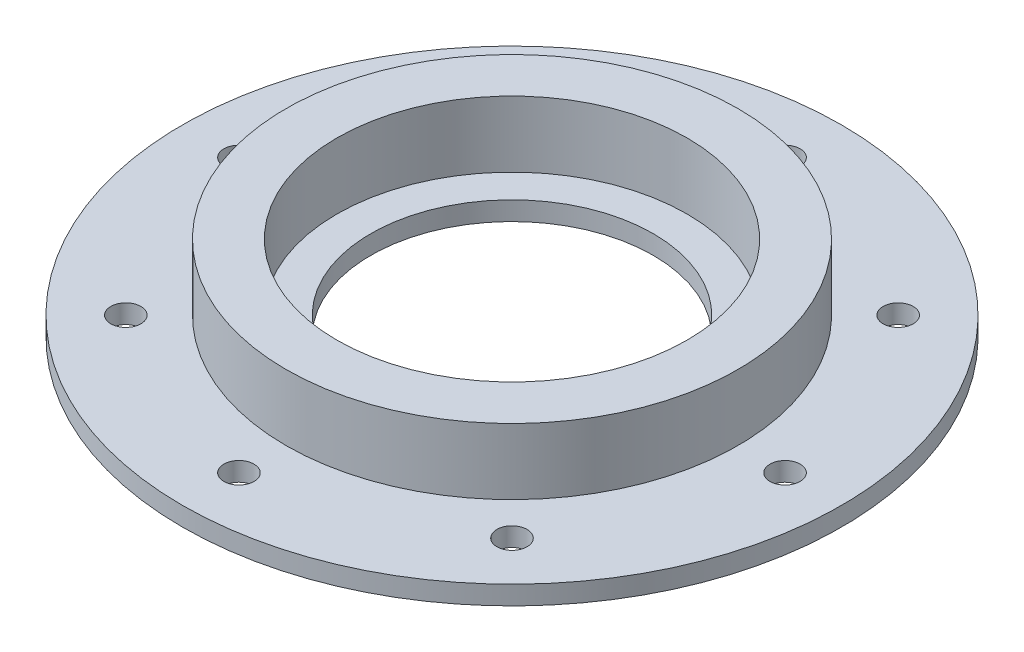
SolidWorks part; units mm, degrees
ref_plane "前视基准面" through (0, 0, 0) normal (0, 0, 1) x (1, 0, 0)
ref_plane "上视基准面" through (0, 0, 0) normal (0, 1, 0) x (1, 0, 0)
ref_plane "右视基准面" through (0, 0, 0) normal (1, 0, 0) x (0, 0, -1)
sketch "草图1" plane through (0, 0, 0) normal (0, 1, 0) x (1, 0, 0)
  line L0 (0, 0) -> (29, 0) construction
  circle A0 centre (0, 0) radius 15
  circle A1 centre (0, 0) radius 35
  circle A2 centre (29, 0) radius 1.6
  circle A3 centre (20.5061, -20.5061) radius 1.6
  circle A4 centre (0, -29) radius 1.6
  circle A5 centre (-20.5061, -20.5061) radius 1.6
  circle A6 centre (-29, 0) radius 1.6
  circle A7 centre (-20.5061, 20.5061) radius 1.6
  circle A8 centre (0, 29) radius 1.6
  circle A9 centre (20.5061, 20.5061) radius 1.6
  dimension "D1" = 70
  dimension "D2" = 30
  dimension "D3" = 3.2
  dimension "D4" = 29
  dimension "D5" = 8
extrude "凸台-拉伸1" add sketch "草图1" against normal blind 2
sketch "草图2" plane through (0, 0, 0) normal (0, 1, 0) x (1, 0, 0)
  circle A0 centre (0, 0) radius 18.6
  circle A1 centre (0, 0) radius 24
  dimension "D1" = 37.2
  dimension "D2" = 48
extrude "凸台-拉伸2" add sketch "草图2" along normal blind 7
